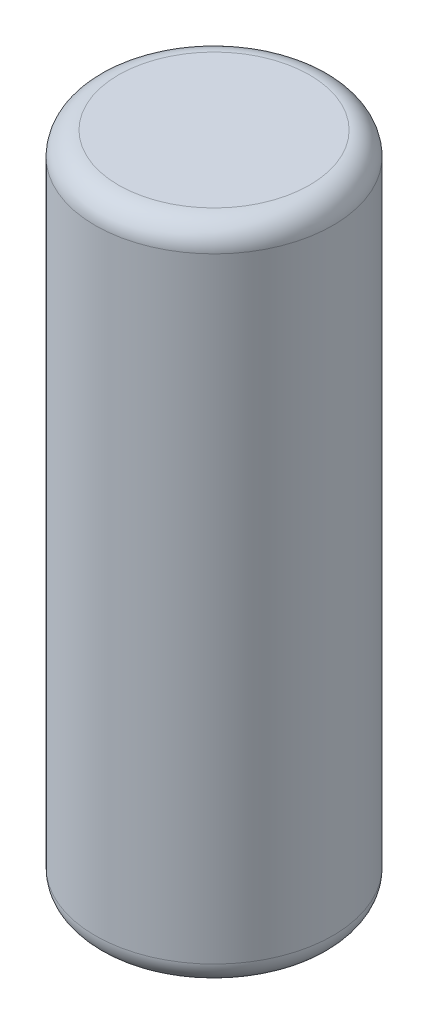
SolidWorks part; units mm, degrees
ref_plane "Front Plane" through (0, 0, 0) normal (0, 0, 1) x (1, 0, 0)
ref_plane "Top Plane" through (0, 0, 0) normal (0, 1, 0) x (1, 0, 0)
ref_plane "Right Plane" through (0, 0, 0) normal (1, 0, 0) x (0, 0, -1)
sketch "Sketch2" plane through (0, 0, 0) normal (0, 1, 0) x (1, 0, 0)
  circle A0 centre (0, 0) radius 51
  dimension "D1" = 102
extrude "Boss-Extrude1" add sketch "Sketch2" along normal blind 284
fillet "Fillet1" radius 10 2 edges at (0, 0, 51) (0, 284, 51)
